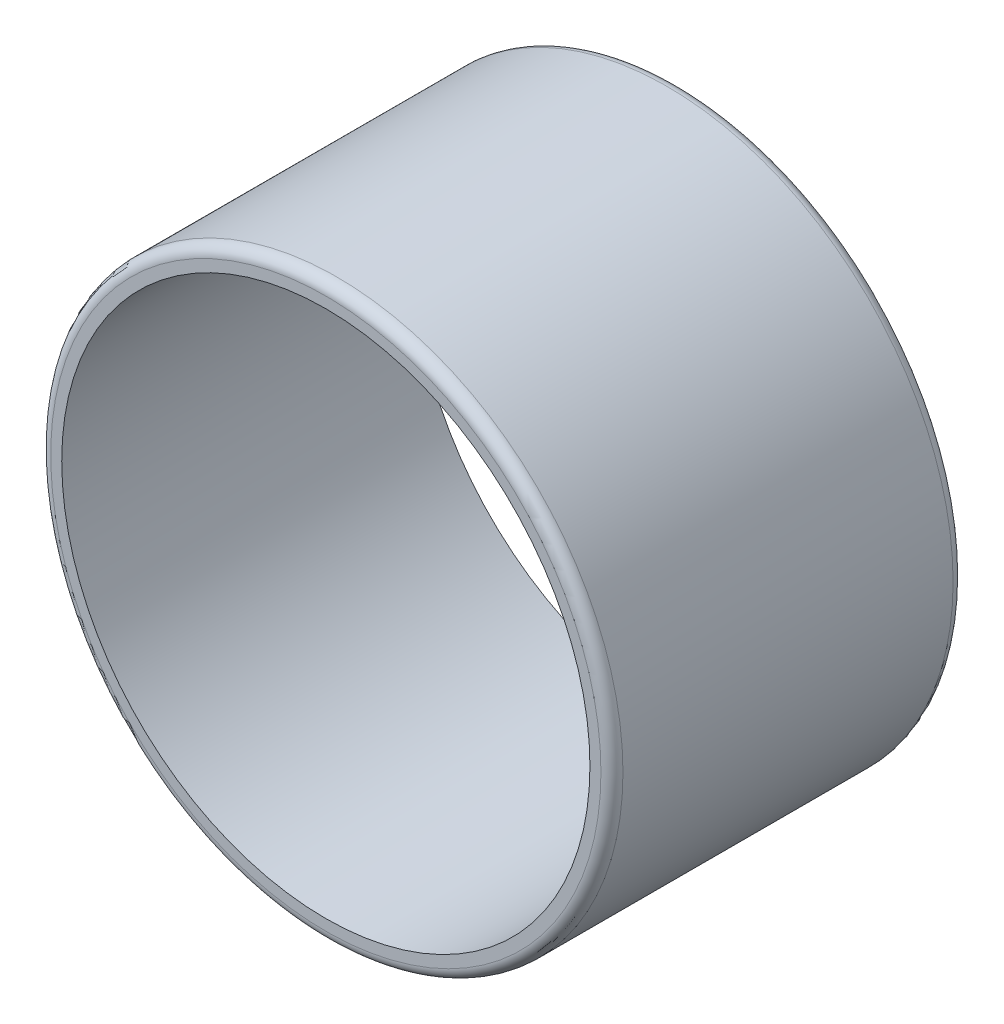
SolidWorks part; units mm, degrees
ref_plane "Face" through (0, 0, 0) normal (0, 0, 1) x (1, 0, 0)
ref_plane "Dessus" through (0, 0, 0) normal (0, 1, 0) x (1, 0, 0)
ref_plane "Droite" through (0, 0, 0) normal (1, 0, 0) x (0, 0, -1)
sketch "Esquisse1" plane through (0, 0, 0) normal (0, 0, 1) x (1, 0, 0)
  circle A0 centre (0, 0) radius 12
  circle A1 centre (0, 0) radius 13
  dimension "D1" = 24
  dimension "D2" = 26
extrude "Extrusion1" add sketch "Esquisse1" along normal mid plane 16
fillet "Congé1" radius 0.5 2 edges at (13, 0, -8) (13, 0, 8)
